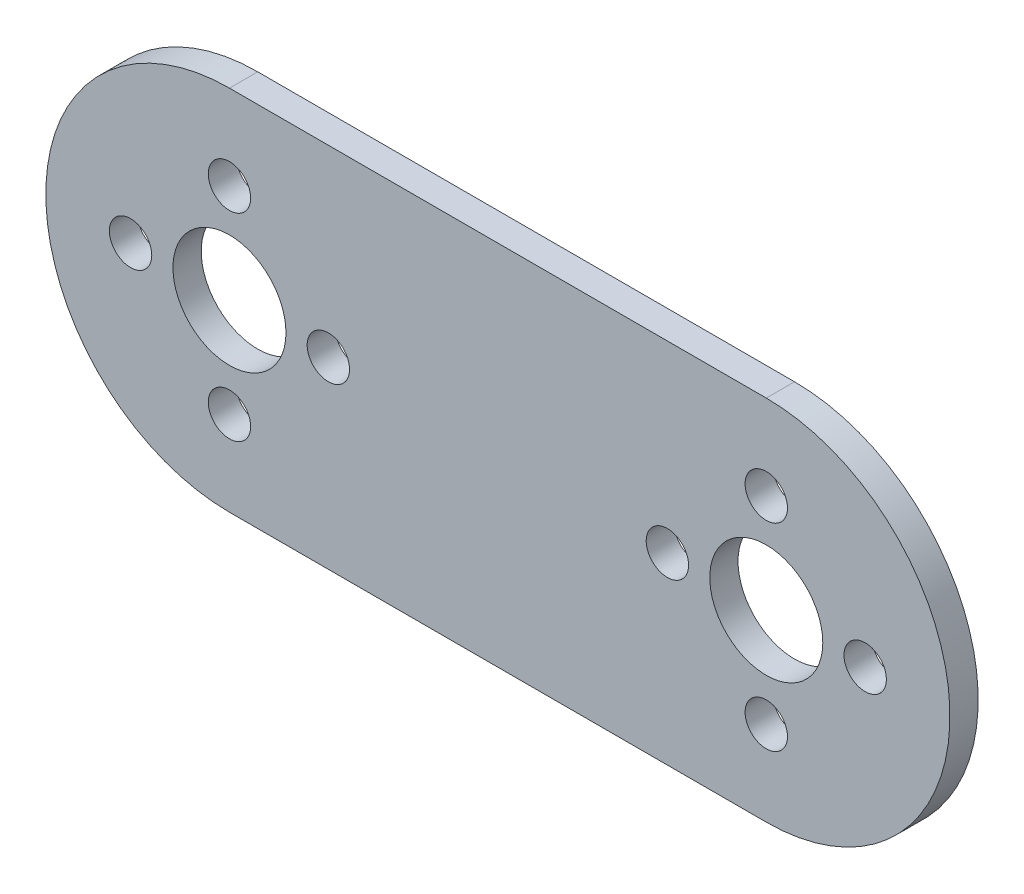
SolidWorks part; units mm, degrees
ref_plane "前视基准面" through (0, 0, 0) normal (0, 0, 1) x (1, 0, 0)
ref_plane "上视基准面" through (0, 0, 0) normal (0, 1, 0) x (1, 0, 0)
ref_plane "右视基准面" through (0, 0, 0) normal (1, 0, 0) x (0, 0, -1)
sketch "草图1" plane through (0, 0, 0) normal (0, 0, 1) x (1, 0, 0)
  line L1 (-19, -13) -> (19, -13)
  line L3 (-19, 13) -> (19, 13)
  arc A0 (19, 13) -> (19, -13) centre (19, 0) cw
  arc A1 (-19, -13) -> (-19, 13) centre (-19, 0) cw
  circle A4 centre (-19, 0) radius 4
  circle A5 centre (19, 0) radius 4
  circle A6 centre (-19, 7) radius 1.5
  circle A7 centre (19, 7) radius 1.5
  circle A8 centre (-12, 0) radius 1.5
  circle A9 centre (-19, -7) radius 1.5
  circle A10 centre (-26, 0) radius 1.5
  circle A11 centre (26, 0) radius 1.5
  circle A12 centre (19, -7) radius 1.5
  circle A13 centre (12, 0) radius 1.5
  point P0 (0, 0)
  point P23 (-19, 0)
  point P30 (19, 0)
  dimension "D1" = 4
  dimension "D2" = 4
extrude "凸台-拉伸1" add sketch "草图1" along normal blind 2
